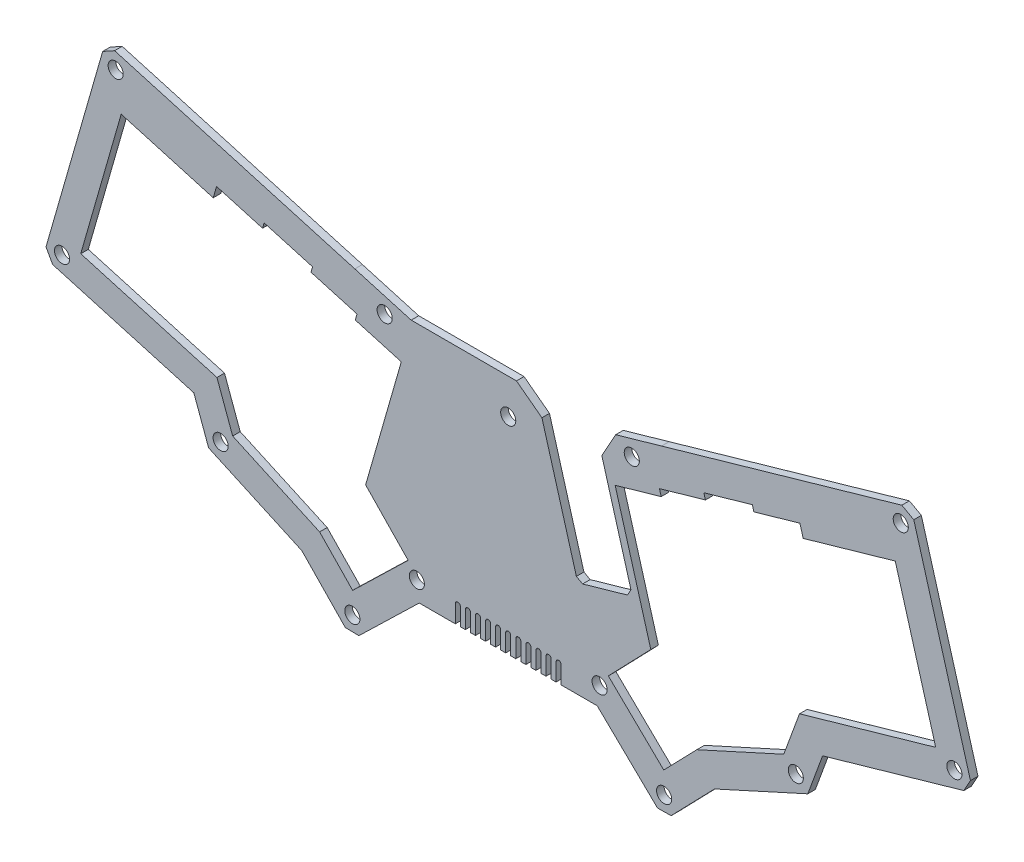
SolidWorks part; units mm, degrees
ref_plane "Plan de face" through (0, 0, 0) normal (0, 0, 1) x (1, 0, 0)
ref_plane "Plan de dessus" through (0, 0, 0) normal (0, 1, 0) x (1, 0, 0)
ref_plane "Plan de droite" through (0, 0, 0) normal (1, 0, 0) x (0, 0, -1)
sketch "Esquisse1" plane through (0, 0, 0) normal (0, 0, 1) x (1, 0, 0)
  line L0 (-121.6461, -32.0475) -> (-108.1875, -28.1884) construction
  line L1 (-108.1875, -28.1884) -> (-104.3283, -41.647) construction
  line L2 (-104.3283, -41.647) -> (-117.7869, -45.5062) construction
  line L3 (-117.7869, -45.5062) -> (-121.6461, -32.0475) construction
  line L4 (-100.1763, -37.9855) -> (-104.0355, -24.5269) construction
  line L5 (-104.0355, -24.5269) -> (-90.5769, -20.6677) construction
  line L6 (-90.5769, -20.6677) -> (-86.7177, -34.1263) construction
  line L7 (-86.7177, -34.1263) -> (-100.1763, -37.9855) construction
  line L8 (-82.5657, -30.4649) -> (-86.4249, -17.0063) construction
  line L9 (-86.4249, -17.0063) -> (-72.9663, -13.1471) construction
  line L10 (-72.9663, -13.1471) -> (-69.1071, -26.6057) construction
  line L11 (-69.1071, -26.6057) -> (-82.5657, -30.4649) construction
  line L12 (-63.6458, -27.5106) -> (-67.505, -14.0519) construction
  line L13 (-67.505, -14.0519) -> (-54.0463, -10.1927) construction
  line L14 (-54.0463, -10.1927) -> (-50.1872, -23.6514) construction
  line L15 (-50.1872, -23.6514) -> (-63.6458, -27.5106) construction
  line L16 (-44.0711, -26.8394) -> (-47.9303, -13.3808) construction
  line L17 (-47.9303, -13.3808) -> (-34.4717, -9.5216) construction
  line L18 (-34.4717, -9.5216) -> (-30.6125, -22.9802) construction
  line L19 (-30.6125, -22.9802) -> (-44.0711, -26.8394) construction
  line L20 (-25.8054, -21.6018) -> (-29.6646, -8.1432) construction
  line L21 (-29.6646, -8.1432) -> (-16.206, -4.284) construction
  line L22 (-16.206, -4.284) -> (-12.3468, -17.7426) construction
  line L23 (-12.3468, -17.7426) -> (-25.8054, -21.6018) construction
  line L24 (-116.4086, -50.3128) -> (-102.95, -46.4536) construction
  line L25 (-102.95, -46.4536) -> (-99.0908, -59.9122) construction
  line L26 (-99.0908, -59.9122) -> (-112.5494, -63.7714) construction
  line L27 (-112.5494, -63.7714) -> (-116.4086, -50.3128) construction
  line L28 (-98.798, -42.7922) -> (-85.3394, -38.933) construction
  line L29 (-85.3394, -38.933) -> (-81.4802, -52.3916) construction
  line L30 (-81.4802, -52.3916) -> (-94.9388, -56.2508) construction
  line L31 (-94.9388, -56.2508) -> (-98.798, -42.7922) construction
  line L32 (-81.1874, -35.2715) -> (-67.7288, -31.4123) construction
  line L33 (-67.7288, -31.4123) -> (-63.8696, -44.8709) construction
  line L34 (-63.8696, -44.8709) -> (-77.3282, -48.7301) construction
  line L35 (-77.3282, -48.7301) -> (-81.1874, -35.2715) construction
  line L36 (-62.2675, -32.3172) -> (-48.8089, -28.458) construction
  line L37 (-48.8089, -28.458) -> (-44.9497, -41.9166) construction
  line L38 (-44.9497, -41.9166) -> (-58.4083, -45.7758) construction
  line L39 (-58.4083, -45.7758) -> (-62.2675, -32.3172) construction
  line L40 (-42.6928, -31.646) -> (-29.2342, -27.7869) construction
  line L41 (-29.2342, -27.7869) -> (-25.375, -41.2455) construction
  line L42 (-25.375, -41.2455) -> (-38.8336, -45.1047) construction
  line L43 (-38.8336, -45.1047) -> (-42.6928, -31.646) construction
  line L44 (-24.4271, -26.4084) -> (-10.9685, -22.5492) construction
  line L45 (-10.9685, -22.5492) -> (-7.1093, -36.0078) construction
  line L46 (-7.1093, -36.0078) -> (-20.5679, -39.867) construction
  line L47 (-20.5679, -39.867) -> (-24.4271, -26.4084) construction
  line L48 (-19.1896, -44.6737) -> (-5.731, -40.8145) construction
  line L49 (-5.731, -40.8145) -> (-1.8718, -54.2731) construction
  line L50 (-1.8718, -54.2731) -> (-15.3304, -58.1323) construction
  line L51 (-15.3304, -58.1323) -> (-19.1896, -44.6737) construction
  line L52 (-37.4554, -49.9113) -> (-23.9967, -46.0521) construction
  line L53 (-23.9967, -46.0521) -> (-20.1376, -59.5107) construction
  line L54 (-20.1376, -59.5107) -> (-33.5962, -63.3699) construction
  line L55 (-33.5962, -63.3699) -> (-37.4554, -49.9113) construction
  line L56 (-57.03, -50.5825) -> (-43.5714, -46.7233) construction
  line L57 (-43.5714, -46.7233) -> (-39.7122, -60.1819) construction
  line L58 (-39.7122, -60.1819) -> (-53.1708, -64.0411) construction
  line L59 (-53.1708, -64.0411) -> (-57.03, -50.5825) construction
  line L60 (-75.9499, -53.5368) -> (-62.4913, -49.6776) construction
  line L61 (-62.4913, -49.6776) -> (-58.6321, -63.1362) construction
  line L62 (-58.6321, -63.1362) -> (-72.0908, -66.9954) construction
  line L63 (-72.0908, -66.9954) -> (-75.9499, -53.5368) construction
  line L64 (-93.5605, -61.0574) -> (-80.1019, -57.1982) construction
  line L65 (-80.1019, -57.1982) -> (-76.2427, -70.6569) construction
  line L66 (-76.2427, -70.6569) -> (-89.7013, -74.516) construction
  line L67 (-89.7013, -74.516) -> (-93.5605, -61.0574) construction
  line L68 (-111.1711, -68.5781) -> (-97.7125, -64.7189) construction
  line L69 (-97.7125, -64.7189) -> (-93.8533, -78.1775) construction
  line L70 (-93.8533, -78.1775) -> (-107.3119, -82.0367) construction
  line L71 (-107.3119, -82.0367) -> (-111.1711, -68.5781) construction
  line L72 (-79.0181, -77.3048) -> (-65.5595, -73.4456) construction
  line L73 (-65.5595, -73.4456) -> (-61.7003, -86.9042) construction
  line L74 (-61.7003, -86.9042) -> (-75.1589, -90.7634) construction
  line L75 (-75.1589, -90.7634) -> (-79.0181, -77.3048) construction
  line L76 (-99.4001, -88.1351) -> (-87.3916, -80.9362)
  line L77 (-87.3916, -80.9362) -> (-80.1927, -92.9448)
  line L78 (-80.1927, -92.9448) -> (-92.2012, -100.1436)
  line L79 (-92.2012, -100.1436) -> (-99.4001, -88.1351)
  line L80 (-120.0498, -100.4367) -> (-110.317, -90.3719)
  line L81 (-110.317, -90.3719) -> (-100.2522, -100.1047)
  line L82 (-100.2522, -100.1047) -> (-109.985, -110.1695)
  line L83 (-109.985, -110.1695) -> (-120.0498, -100.4367)
  line L86 (0.634, -55.7756) -> (-52.9527, -71.1413) construction
  line L89 (-59.2205, -88.2424) -> (-52.9527, -71.1413) construction
  line L96 (-93.4066, -103.0586) -> (-59.4637, -88.3612) construction
  line L97 (-105.418, -115.2057) -> (-93.9754, -103.3509) construction
  line L98 (-126.5332, -96.9919) -> (-107.5003, -115.385) construction
  line L99 (-167.7972, -50.1766) -> (-183.2082, -64.014) construction
  line L100 (-106.3822, -25.4572) -> (-123.6848, -30.4187) construction
  line L101 (-72.1178, -10.6906) -> (-88.4663, -15.3784) construction
  line L102 (-53.2337, -7.6163) -> (-70.5393, -12.5786) construction
  line L103 (-33.6604, -6.9452) -> (-50.9661, -11.9075) construction
  line L104 (-15.3965, -1.7081) -> (-31.745, -6.396) construction
  line L105 (0.5403, -55.2132) -> (-14.6896, -2.0999) construction
  line L106 (-16.199, -60.6113) -> (0.1495, -55.9235) construction
  line L107 (-52.7198, -71.0835) -> (-18.1144, -61.1606) construction
  line L108 (-59.1184, -88.0534) -> (-52.9674, -71.2752) construction
  line L109 (-183.2082, -64.014) -> (-173.1824, -64.9357) construction
  line L113 (-102.2678, -134.438) -> (-84.7238, -116.3191) construction
  line L114 (-84.7238, -116.3191) -> (-47.2969, -99.2981) construction
  line L115 (-47.2969, -99.2981) -> (-41.4917, -83.4594) construction
  line L116 (14.3812, -67.4381) -> (-41.4917, -83.4594) construction
  line L117 (17.8093, -61.2536) -> (-5.1371, 18.7701) construction
  line L122 (-11.3217, 22.1985) -> (-107.4545, -5.3614) construction
  line L129 (-167.7953, -27.6055) -> (-167.7953, -64.7189) construction
  line L130 (-242.0685, -103.8419) -> (-276.37, -88.2424) construction
  line L131 (-229.5108, -116.8112) -> (-242.0685, -103.8419) construction
  line L138 (-208.9328, -96.8551) -> (-229.5108, -116.8112) construction
  line L139 (-225.5107, -79.6567) -> (-208.9328, -96.8551) construction
  line L140 (-109.3352, -134.5492) -> (-102.2678, -134.438) construction
  line L142 (-5.1371, 18.7701) -> (-11.3217, 22.1985) construction
  line L143 (-211.4691, -30.6868) -> (-225.5107, -79.6567) construction
  line L147 (-114.18, -7.2899) -> (-107.4545, -5.3614) construction
  line L148 (-114.18, -7.2899) -> (-123.7936, -10.0465) construction
  line L154 (-4.3102, 15.8863) -> (-127.3606, -19.3904) construction
  line L155 (-131.531, -101.8802) -> (-105.9239, -126.7133) construction
  line L156 (-105.9239, -126.7133) -> (-89.4162, -109.6646) construction
  line L157 (-128.0696, -96.8789) -> (-106.0575, -118.2258)
  line L158 (-106.0575, -118.2258) -> (-92.9354, -104.6737)
  line L159 (-92.9354, -104.6737) -> (-58.4256, -88.9794)
  line L160 (-58.4256, -88.9794) -> (-52.1886, -71.9625)
  line L161 (1.8709, -56.4612) -> (-52.1886, -71.9625)
  line L162 (1.8709, -56.4612) -> (-14.1861, -0.4639)
  line L163 (-14.1861, -0.4639) -> (-50.7166, -10.9388)
  line L164 (-50.7166, -10.9388) -> (-52.026, -6.3725)
  line L165 (-52.026, -6.3725) -> (-70.2913, -11.61)
  line L166 (-70.2913, -11.61) -> (-70.911, -9.4488)
  line L167 (-70.911, -9.4488) -> (-90.1377, -14.9608)
  line L168 (-90.1377, -14.9608) -> (-89.5177, -17.1231)
  line L169 (-89.5177, -17.1231) -> (-107.783, -22.3606)
  line L170 (-107.783, -22.3606) -> (-107.0938, -24.7639)
  line L171 (-107.0938, -24.7639) -> (-125.3583, -30.0011)
  line L172 (-125.3583, -30.0011) -> (-111.2001, -79.378)
  line L173 (-111.2001, -79.378) -> (-127.3777, -96.1611)
  line L174 (-89.4162, -109.6646) -> (-53.6562, -93.4017) construction
  line L175 (-53.6562, -93.4017) -> (-47.6042, -76.8897) construction
  line L176 (9.2923, -60.5749) -> (-47.6042, -76.8897) construction
  line L177 (9.2923, -60.5749) -> (-12.0005, 13.6817) construction
  line L178 (-229.7336, -25.4495) -> (-211.4691, -30.6868) construction
  line L179 (-229.0444, -23.0462) -> (-229.7336, -25.4495) construction
  line L180 (-173.1824, -64.9357) -> (-167.7972, -60.1004) construction
  line L181 (-247.3097, -17.8087) -> (-229.0444, -23.0462) construction
  line L185 (17.8093, -61.2536) -> (14.3812, -67.4381) construction
  line L186 (-183.2987, -65.7677) -> (-173.2729, -66.6895) construction
  line L187 (-173.2729, -66.6895) -> (-167.8052, -74.7882) construction
  line L190 (-246.6897, -15.6465) -> (-247.3097, -17.8087) construction
  line L191 (-263.9939, -10.6857) -> (-246.6897, -15.6465) construction
  line L192 (-264.6136, -12.8469) -> (-263.9939, -10.6857) construction
  line L193 (-282.8789, -7.6094) -> (-264.6136, -12.8469) construction
  line L194 (-284.1883, -12.1757) -> (-282.8789, -7.6094) construction
  line L195 (-320.7188, -1.7008) -> (-284.1883, -12.1757) construction
  line L196 (-336.2245, -55.7756) -> (-320.7188, -1.7008) construction
  line L197 (-183.2987, -65.7677) -> (-167.8052, -88.0782) construction
  line L198 (-181.8414, -71.5322) -> (-174.8684, -81.0171) construction
  line L199 (-174.8684, -81.0171) -> (-178.3549, -83.9622) construction
  line L200 (-344.8828, -60.5749) -> (-323.5901, 13.6817) construction
  line L201 (-344.8828, -60.5749) -> (-287.9863, -76.8897) construction
  line L202 (-281.9343, -93.4017) -> (-287.9863, -76.8897) construction
  line L203 (-246.1743, -109.6646) -> (-281.9343, -93.4017) construction
  line L204 (-224.3904, -79.378) -> (-208.2128, -96.1611)
  line L205 (-210.2322, -30.0011) -> (-224.3904, -79.378)
  line L206 (-228.4967, -24.7639) -> (-210.2322, -30.0011)
  line L207 (-227.8075, -22.3606) -> (-228.4967, -24.7639)
  line L208 (-246.0728, -17.1231) -> (-227.8075, -22.3606)
  line L209 (-245.4528, -14.9608) -> (-246.0728, -17.1231)
  line L210 (-264.6796, -9.4488) -> (-245.4528, -14.9608)
  line L211 (-265.2993, -11.61) -> (-264.6796, -9.4488)
  line L212 (-283.5645, -6.3725) -> (-265.2993, -11.61)
  line L213 (-284.8739, -10.9388) -> (-283.5645, -6.3725)
  line L217 (0.634, -55.7756) -> (-14.8717, -1.7008) construction
  line L220 (-14.8717, -1.7008) -> (-51.4022, -12.1757) construction
  line L221 (-51.4022, -12.1757) -> (-52.7116, -7.6094) construction
  line L222 (-52.7116, -7.6094) -> (-70.9769, -12.8469) construction
  line L223 (-70.9769, -12.8469) -> (-71.5966, -10.6857) construction
  line L224 (-71.5966, -10.6857) -> (-88.9008, -15.6465) construction
  line L225 (-88.9008, -15.6465) -> (-88.2808, -17.8087) construction
  line L226 (-88.2808, -17.8087) -> (-106.5461, -23.0462) construction
  line L227 (-106.5461, -23.0462) -> (-105.8569, -25.4495) construction
  line L228 (-105.8569, -25.4495) -> (-124.1214, -30.6868) construction
  line L231 (-124.1214, -30.6868) -> (-110.0799, -79.6567) construction
  line L232 (-110.0799, -79.6567) -> (-126.6577, -96.8551) construction
  line L233 (-126.6577, -96.8551) -> (-106.0797, -116.8112) construction
  line L234 (-106.0797, -116.8112) -> (-93.522, -103.8419) construction
  line L235 (-93.522, -103.8419) -> (-59.2205, -88.2424) construction
  line L236 (-321.4044, -0.4639) -> (-284.8739, -10.9388)
  line L237 (-337.4614, -56.4612) -> (-321.4044, -0.4639)
  line L238 (-337.4614, -56.4612) -> (-283.4019, -71.9625)
  line L239 (-277.1649, -88.9794) -> (-283.4019, -71.9625)
  line L240 (-242.6551, -104.6737) -> (-277.1649, -88.9794)
  line L241 (-229.5331, -118.2258) -> (-242.6551, -104.6737)
  line L242 (-208.2366, -97.573) -> (-229.5331, -118.2258)
  line L243 (-229.6666, -126.7133) -> (-246.1743, -109.6646) construction
  line L244 (-204.0596, -101.8802) -> (-229.6666, -126.7133) construction
  line L245 (-331.2803, 15.8863) -> (-208.2299, -19.3904) construction
  line L246 (-178.3549, -83.9622) -> (-185.8788, -75.0552) construction
  line L247 (-185.8788, -75.0552) -> (-181.8414, -71.5322) construction
  line L248 (-176.7625, -46.6332) -> (-185.5498, -54.5291) construction
  line L249 (-185.5498, -54.5291) -> (-181.1562, -59.4188) construction
  line L250 (-181.1562, -59.4188) -> (-172.3689, -51.5229) construction
  line L251 (-276.4721, -88.0534) -> (-282.6232, -71.2752) construction
  line L252 (-282.8707, -71.0835) -> (-317.4761, -61.1606) construction
  line L253 (-319.3915, -60.6113) -> (-335.74, -55.9235) construction
  line L254 (-336.1309, -55.2132) -> (-320.9009, -2.0999) construction
  line L255 (-320.194, -1.7081) -> (-303.8455, -6.396) construction
  line L256 (-301.9301, -6.9452) -> (-284.6245, -11.9075) construction
  line L257 (-282.3568, -7.6163) -> (-265.0512, -12.5786) construction
  line L258 (-263.4727, -10.6906) -> (-247.1242, -15.3784) construction
  line L259 (-229.2083, -25.4572) -> (-211.9057, -30.4187) construction
  line L260 (-172.3689, -51.5229) -> (-176.7625, -46.6332) construction
  line L261 (-209.0573, -96.9919) -> (-228.0902, -115.385) construction
  line L262 (-230.1725, -115.2057) -> (-241.6151, -103.3509) construction
  line L263 (-242.1839, -103.0586) -> (-276.1268, -88.3612) construction
  line L264 (-276.37, -88.2424) -> (-282.6379, -71.1413) construction
  line L265 (-336.2245, -55.7756) -> (-282.6379, -71.1413) construction
  line L268 (-353.3998, -61.2536) -> (-349.9717, -67.4381) construction
  line L274 (-221.4105, -7.2899) -> (-206.0252, -11.7015) construction
  line L275 (-221.4105, -7.2899) -> (-228.136, -5.3614) construction
  line L276 (-330.4534, 18.7701) -> (-324.2688, 22.1985) construction
  line L277 (-226.2553, -134.5492) -> (-233.3227, -134.438) construction
  line L281 (-324.2688, 22.1985) -> (-228.136, -5.3614) construction
  line L282 (-353.3998, -61.2536) -> (-330.4534, 18.7701) construction
  line L283 (-349.9717, -67.4381) -> (-294.0988, -83.4594) construction
  line L284 (-288.2936, -99.2981) -> (-294.0988, -83.4594) construction
  line L285 (-250.8667, -116.3191) -> (-288.2936, -99.2981) construction
  line L286 (-233.3227, -134.438) -> (-250.8667, -116.3191) construction
  line L288 (-225.6055, -110.1695) -> (-215.5407, -100.4367) construction
  line L289 (-235.3383, -100.1047) -> (-225.6055, -110.1695) construction
  line L290 (-225.2735, -90.3719) -> (-235.3383, -100.1047) construction
  line L291 (-215.5407, -100.4367) -> (-225.2735, -90.3719) construction
  line L292 (-243.3893, -100.1436) -> (-236.1904, -88.1351) construction
  line L293 (-255.3978, -92.9448) -> (-243.3893, -100.1436) construction
  line L294 (-248.1989, -80.9362) -> (-255.3978, -92.9448) construction
  line L295 (-236.1904, -88.1351) -> (-248.1989, -80.9362) construction
  line L296 (-260.4316, -90.7634) -> (-256.5724, -77.3048) construction
  line L297 (-273.8902, -86.9042) -> (-260.4316, -90.7634) construction
  line L298 (-270.031, -73.4456) -> (-273.8902, -86.9042) construction
  line L299 (-256.5724, -77.3048) -> (-270.031, -73.4456) construction
  line L300 (-228.2786, -82.0367) -> (-224.4194, -68.5781) construction
  line L301 (-241.7372, -78.1775) -> (-228.2786, -82.0367) construction
  line L302 (-237.878, -64.7189) -> (-241.7372, -78.1775) construction
  line L303 (-224.4194, -68.5781) -> (-237.878, -64.7189) construction
  line L304 (-245.8892, -74.516) -> (-242.03, -61.0574) construction
  line L305 (-259.3478, -70.6569) -> (-245.8892, -74.516) construction
  line L306 (-255.4886, -57.1982) -> (-259.3478, -70.6569) construction
  line L307 (-242.03, -61.0574) -> (-255.4886, -57.1982) construction
  line L308 (-263.4998, -66.9954) -> (-259.6406, -53.5368) construction
  line L309 (-276.9584, -63.1362) -> (-263.4998, -66.9954) construction
  line L310 (-273.0992, -49.6776) -> (-276.9584, -63.1362) construction
  line L311 (-259.6406, -53.5368) -> (-273.0992, -49.6776) construction
  line L312 (-282.4197, -64.0411) -> (-278.5605, -50.5825) construction
  line L313 (-295.8783, -60.1819) -> (-282.4197, -64.0411) construction
  line L314 (-292.0191, -46.7233) -> (-295.8783, -60.1819) construction
  line L315 (-278.5605, -50.5825) -> (-292.0191, -46.7233) construction
  line L316 (-301.9944, -63.3699) -> (-298.1352, -49.9113) construction
  line L317 (-315.453, -59.5107) -> (-301.9944, -63.3699) construction
  line L318 (-311.5938, -46.0521) -> (-315.453, -59.5107) construction
  line L319 (-298.1352, -49.9113) -> (-311.5938, -46.0521) construction
  line L320 (-320.2601, -58.1323) -> (-316.4009, -44.6737) construction
  line L321 (-333.7187, -54.2731) -> (-320.2601, -58.1323) construction
  line L322 (-329.8595, -40.8145) -> (-333.7187, -54.2731) construction
  line L323 (-316.4009, -44.6737) -> (-329.8595, -40.8145) construction
  line L324 (-315.0226, -39.867) -> (-311.1634, -26.4084) construction
  line L325 (-328.4812, -36.0078) -> (-315.0226, -39.867) construction
  line L326 (-324.622, -22.5492) -> (-328.4812, -36.0078) construction
  line L327 (-311.1634, -26.4084) -> (-324.622, -22.5492) construction
  line L328 (-296.7569, -45.1047) -> (-292.8977, -31.646) construction
  line L329 (-310.2155, -41.2455) -> (-296.7569, -45.1047) construction
  line L330 (-306.3563, -27.7869) -> (-310.2155, -41.2455) construction
  line L331 (-292.8977, -31.646) -> (-306.3563, -27.7869) construction
  line L332 (-277.1822, -45.7758) -> (-273.323, -32.3172) construction
  line L333 (-290.6408, -41.9166) -> (-277.1822, -45.7758) construction
  line L334 (-286.7817, -28.458) -> (-290.6408, -41.9166) construction
  line L335 (-273.323, -32.3172) -> (-286.7817, -28.458) construction
  line L336 (-258.2623, -48.7301) -> (-254.4031, -35.2715) construction
  line L337 (-271.7209, -44.8709) -> (-258.2623, -48.7301) construction
  line L338 (-267.8617, -31.4123) -> (-271.7209, -44.8709) construction
  line L339 (-254.4031, -35.2715) -> (-267.8617, -31.4123) construction
  line L340 (-240.6517, -56.2508) -> (-236.7925, -42.7922) construction
  line L341 (-254.1103, -52.3916) -> (-240.6517, -56.2508) construction
  line L342 (-250.2511, -38.933) -> (-254.1103, -52.3916) construction
  line L343 (-236.7925, -42.7922) -> (-250.2511, -38.933) construction
  line L344 (-223.0411, -63.7714) -> (-219.1819, -50.3128) construction
  line L345 (-236.4997, -59.9122) -> (-223.0411, -63.7714) construction
  line L346 (-232.6405, -46.4536) -> (-236.4997, -59.9122) construction
  line L347 (-219.1819, -50.3128) -> (-232.6405, -46.4536) construction
  line L348 (-323.2438, -17.7426) -> (-309.7851, -21.6018) construction
  line L349 (-319.3846, -4.284) -> (-323.2438, -17.7426) construction
  line L350 (-305.926, -8.1432) -> (-319.3846, -4.284) construction
  line L351 (-309.7851, -21.6018) -> (-305.926, -8.1432) construction
  line L352 (-304.978, -22.9802) -> (-291.5194, -26.8394) construction
  line L353 (-301.1188, -9.5216) -> (-304.978, -22.9802) construction
  line L354 (-287.6602, -13.3808) -> (-301.1188, -9.5216) construction
  line L355 (-291.5194, -26.8394) -> (-287.6602, -13.3808) construction
  line L356 (-285.4034, -23.6514) -> (-271.9448, -27.5106) construction
  line L357 (-281.5442, -10.1927) -> (-285.4034, -23.6514) construction
  line L358 (-268.0856, -14.0519) -> (-281.5442, -10.1927) construction
  line L359 (-271.9448, -27.5106) -> (-268.0856, -14.0519) construction
  line L360 (-266.4834, -26.6057) -> (-253.0248, -30.4649) construction
  line L361 (-262.6242, -13.1471) -> (-266.4834, -26.6057) construction
  line L362 (-249.1656, -17.0063) -> (-262.6242, -13.1471) construction
  line L363 (-253.0248, -30.4649) -> (-249.1656, -17.0063) construction
  line L364 (-248.8728, -34.1263) -> (-235.4142, -37.9855) construction
  line L365 (-245.0136, -20.6677) -> (-248.8728, -34.1263) construction
  line L366 (-231.555, -24.5269) -> (-245.0136, -20.6677) construction
  line L367 (-235.4142, -37.9855) -> (-231.555, -24.5269) construction
  line L368 (-217.8036, -45.5062) -> (-213.9444, -32.0475) construction
  line L369 (-231.2622, -41.647) -> (-217.8036, -45.5062) construction
  line L370 (-227.4031, -28.1884) -> (-231.2622, -41.647) construction
  line L371 (-213.9444, -32.0475) -> (-227.4031, -28.1884) construction
  line L372 (-226.2553, -134.5492) -> (-194.0347, -103.3509) construction
  line L373 (-109.3352, -134.5492) -> (-141.5559, -103.3509) construction
  line L374 (-141.5559, -103.3509) -> (-194.0347, -103.3509) construction
  line L375 (-167.7972, -50.1766) -> (-152.3861, -64.014) construction
  line L376 (-162.4119, -64.9357) -> (-167.7972, -60.1004) construction
  line L377 (-162.3376, -66.6895) -> (-167.8052, -74.7882) construction
  line L378 (-152.3118, -65.7677) -> (-167.8052, -88.0782) construction
  line L379 (-163.2254, -51.5229) -> (-158.8318, -46.6332) construction
  line L380 (-154.4381, -59.4188) -> (-163.2254, -51.5229) construction
  line L381 (-150.0445, -54.5291) -> (-154.4381, -59.4188) construction
  line L382 (-158.8318, -46.6332) -> (-150.0445, -54.5291) construction
  line L383 (-149.7316, -75.0552) -> (-153.7691, -71.5322) construction
  line L384 (-157.2555, -83.9622) -> (-149.7316, -75.0552) construction
  line L385 (-160.742, -81.0171) -> (-157.2555, -83.9622) construction
  line L386 (-153.7691, -71.5322) -> (-160.742, -81.0171) construction
  line L387 (-152.3118, -65.7677) -> (-162.3376, -66.6895) construction
  line L388 (-152.3861, -64.014) -> (-162.4119, -64.9357) construction
  line L389 (-206.0252, -11.7015) -> (-129.5654, -11.7015) construction
  line L390 (-119.0708, -62.7964) -> (-130.6498, -22.4155)
  line L391 (-123.5545, -47.16) -> (-127.4136, -33.7014) construction
  line L392 (-120.442, -65.2702) -> (-138.2688, -70.3819)
  line L393 (-140.7426, -69.0107) -> (-154.4194, -21.3141)
  line L394 (-167.1758, -11.7015) -> (-206.0252, -11.7015) construction
  line L395 (-154.4194, -21.3141) -> (-167.1758, -11.7015) construction
  line L396 (-123.7936, -10.0465) -> (-130.6498, -22.4155) construction
  line L397 (-138.2688, -70.3819) -> (-140.7426, -69.0107)
  line L398 (-119.0708, -62.7964) -> (-120.442, -65.2702)
  line L399 (-129.5654, -11.7015) -> (-123.7936, -10.0465) construction
  line L400 (-165.8487, -12.7015) -> (-206.1657, -12.7015) construction
  line L401 (-221.6861, -8.2511) -> (-206.1657, -12.7015) construction
  line L402 (-221.6861, -8.2511) -> (-228.4116, -6.3226) construction
  line L403 (-324.1462, 21.1231) -> (-228.4116, -6.3226) construction
  line L404 (-329.6063, 18.0963) -> (-324.1462, 21.1231) construction
  line L405 (-352.3244, -61.1311) -> (-329.6063, 18.0963) construction
  line L406 (-352.3244, -61.1311) -> (-349.2979, -66.591) construction
  line L407 (-349.2979, -66.591) -> (-293.3347, -82.6382) construction
  line L408 (-287.4987, -98.561) -> (-293.3347, -82.6382) construction
  line L409 (-250.2802, -115.4872) -> (-287.4987, -98.561) construction
  line L410 (-232.8926, -133.4446) -> (-250.2802, -115.4872) construction
  line L411 (-226.6535, -133.5428) -> (-232.8926, -133.4446) construction
  line L412 (-226.6535, -133.5428) -> (-194.4395, -102.3509) construction
  line L413 (-141.1511, -102.3509) -> (-194.4395, -102.3509) construction
  line L414 (-108.937, -133.5428) -> (-141.1511, -102.3509) construction
  line L415 (-108.937, -133.5428) -> (-102.6979, -133.4446) construction
  line L416 (-102.6979, -133.4446) -> (-85.3104, -115.4872) construction
  line L417 (-85.3104, -115.4872) -> (-48.0918, -98.561) construction
  line L418 (-48.0918, -98.561) -> (-42.2558, -82.6382) construction
  line L419 (13.7074, -66.591) -> (-42.2558, -82.6382) construction
  line L420 (16.7339, -61.1311) -> (13.7074, -66.591) construction
  line L421 (16.7339, -61.1311) -> (-5.9842, 18.0963) construction
  line L422 (-5.9842, 18.0963) -> (-11.4443, 21.1231) construction
  line L423 (-11.4443, 21.1231) -> (-107.1789, -6.3226) construction
  line L424 (-113.9044, -8.2511) -> (-107.1789, -6.3226) construction
  line L425 (-113.9044, -8.2511) -> (-124.4792, -11.2834) construction
  line L426 (-167.1758, -12.7015) -> (-206.1657, -12.7015) construction
  line L427 (-113.9044, -8.2511) -> (-123.5179, -11.0078) construction
  line L428 (-165.8487, -12.7015) -> (-154.4194, -21.3141) construction
  line L429 (-130.6498, -22.4155) -> (-124.4792, -11.2834) construction
  line L430 (-208.2366, -97.573) -> (-207.4919, -96.8551)
  line L431 (-207.4919, -96.8551) -> (-208.2128, -96.1611)
  line L432 (-127.3777, -96.1611) -> (-128.0696, -96.8789)
  line L433 (-221.9618, -9.2124) -> (-206.3062, -13.7015)
  line L434 (-164.5217, -13.7015) -> (-206.3062, -13.7015)
  line L435 (-166.1833, -13.7015) -> (-155.2884, -21.9114) construction
  line L436 (-141.5897, -69.6845) -> (-155.2884, -21.9114) construction
  line L437 (-138.3914, -71.4574) -> (-141.5897, -69.6845) construction
  line L438 (-119.7682, -66.1172) -> (-138.3914, -71.4574) construction
  line L439 (-117.9954, -62.9189) -> (-119.7682, -66.1172) construction
  line L440 (-117.9954, -62.9189) -> (-129.5744, -22.538) construction
  line L441 (-129.5744, -22.538) -> (-123.8054, -12.1305) construction
  line L442 (-113.6287, -9.2124) -> (-125.1648, -12.5203)
  line L443 (-113.6287, -9.2124) -> (-106.9033, -7.2839)
  line L444 (-11.5669, 20.0477) -> (-106.9033, -7.2839)
  line L445 (-6.8313, 17.4225) -> (-11.5669, 20.0477)
  line L446 (15.6584, -61.0086) -> (-6.8313, 17.4225)
  line L447 (15.6584, -61.0086) -> (13.0336, -65.7439)
  line L448 (13.0336, -65.7439) -> (-43.0198, -81.817)
  line L449 (-48.8867, -97.824) -> (-43.0198, -81.817)
  line L450 (-85.8969, -114.6554) -> (-48.8867, -97.824)
  line L451 (-103.128, -132.4513) -> (-85.8969, -114.6554)
  line L452 (-108.5388, -132.5364) -> (-103.128, -132.4513)
  line L453 (-108.5388, -132.5364) -> (-132.4841, -109.3509)
  line L454 (-140.7463, -101.3509) -> (-194.8443, -101.3509) construction
  line L455 (-227.0517, -132.5364) -> (-203.1064, -109.3509)
  line L456 (-227.0517, -132.5364) -> (-232.4625, -132.4513)
  line L457 (-232.4625, -132.4513) -> (-249.6936, -114.6554)
  line L458 (-249.6936, -114.6554) -> (-286.7038, -97.824)
  line L459 (-286.7038, -97.824) -> (-292.5707, -81.817)
  line L460 (-348.6241, -65.7439) -> (-292.5707, -81.817)
  line L461 (-351.2489, -61.0086) -> (-348.6241, -65.7439)
  line L462 (-351.2489, -61.0086) -> (-328.7592, 17.4225)
  line L463 (-328.7592, 17.4225) -> (-324.0237, 20.0477)
  line L464 (-324.0237, 20.0477) -> (-228.6872, -7.2839)
  line L465 (-221.9618, -9.2124) -> (-228.6872, -7.2839)
  line L466 (-166.1833, -13.7015) -> (-206.3062, -13.7015) construction
  line L467 (-113.6287, -9.2124) -> (-123.8054, -12.1305) construction
  line L468 (-130.6498, -22.4155) -> (-125.1648, -12.5203)
  line L469 (-154.4194, -21.3141) -> (-164.5217, -13.7015)
  line L470 (-132.4841, -109.3509) -> (-203.1064, -109.3509)
  line L471 (-140.7463, -109.3509) -> (-194.8443, -109.3509) construction
  line L473 (-227.0517, -132.5364) -> (-194.8443, -101.3509) construction
  line L474 (-108.5388, -132.5364) -> (-140.7463, -101.3509) construction
  circle A2 centre (-12.0005, 13.6817) radius 1.6 construction
  circle A3 centre (-12.0005, 13.6817) radius 3
  circle A4 centre (-118.7579, -16.9241) radius 3
  circle A5 centre (9.2923, -60.5749) radius 3
  circle A6 centre (-53.6562, -93.4017) radius 3
  circle A7 centre (-105.9239, -126.7133) radius 3
  circle A8 centre (-131.531, -101.8802) radius 3
  circle A10 centre (-147.4897, -45.973) radius 1.6 construction
  circle A11 centre (-323.5901, 13.6817) radius 3
  circle A12 centre (-188.1008, -45.973) radius 1.6 construction
  circle A14 centre (-204.0596, -101.8802) radius 3
  circle A15 centre (-229.6666, -126.7133) radius 3
  circle A16 centre (-281.9343, -93.4017) radius 3
  circle A17 centre (-344.8828, -60.5749) radius 3
  circle A18 centre (-216.8326, -16.9241) radius 3
  circle A19 centre (-323.5901, 13.6817) radius 1.6 construction
  circle A20 centre (-167.7953, -27.6055) radius 3
  point P138 (-167.7953, -27.6055)
  point P139 (-6.5153, 23.5764)
  point P150 (-169.1046, -23.0392)
  point P200 (19.1875, -66.0599)
  point P203 (-141.5228, -71.3355)
  point P204 (-141.5228, 1.5705)
  point P263 (-133.4062, -12.8029)
  point P264 (-118.5195, -64.7189)
  point P283 (-140.1914, -70.9332)
  point P284 (-157.1758, -11.7015)
  point P405 (-354.778, -66.0599)
  point P406 (-329.0752, 23.5764)
  dimension "D3" = 3.2
  dimension "D4" = 6
  dimension "D6" = 6
  dimension "D7" = 6
  dimension "D8" = 6
  dimension "D9" = 6
  dimension "D10" = 6
  dimension "D16" = 3.2
  dimension "D14" = 6
  dimension "D2" = 6
  dimension "D5" = 1
  dimension "D11" = 1
  dimension "D18" = 8
extrude "Boss.-Extru.1" add sketch "Esquisse1" along normal blind 3 contours L433 L465 L464 L463 L462 L461 L460 L459 L458 L457 L456 L455 L454 L453 L452 L451 L450 L449 L448 L447 L446 L445 L444 L443 L442 L441 L440 L439 L438 L437 L436 L435 L434 A18 A16 A14 L432 L173 L172 L171 L170 L169 L168 L167 L166 L165 L164
sketch "Esquisse2" plane through (0, 0, 3) normal (0, 0, 1) x (1, 0, 0)
  line L0 (-167.7953, -109.3509) -> (-167.7953, -102.3509) construction
  line L1 (-132.4841, -109.3509) -> (-203.1064, -109.3509) construction
  line L2 (-168.7953, -109.3509) -> (-168.7953, -102.3509)
  line L3 (-166.7953, -109.3509) -> (-166.7953, -102.3509)
  line L4 (-163.7953, -109.3509) -> (-163.7953, -102.3509) construction
  line L5 (-164.7953, -109.3509) -> (-164.7953, -102.3509)
  line L6 (-162.7953, -109.3509) -> (-162.7953, -102.3509)
  line L7 (-159.7953, -109.3509) -> (-159.7953, -102.3509) construction
  line L8 (-160.7953, -109.3509) -> (-160.7953, -102.3509)
  line L9 (-158.7953, -109.3509) -> (-158.7953, -102.3509)
  line L10 (-155.7953, -109.3509) -> (-155.7953, -102.3509) construction
  line L11 (-156.7953, -109.3509) -> (-156.7953, -102.3509)
  line L12 (-154.7953, -109.3509) -> (-154.7953, -102.3509)
  line L13 (-151.7953, -109.3509) -> (-151.7953, -102.3509) construction
  line L14 (-152.7953, -109.3509) -> (-152.7953, -102.3509)
  line L15 (-150.7953, -109.3509) -> (-150.7953, -102.3509)
  line L16 (-147.7953, -109.3509) -> (-147.7953, -102.3509) construction
  line L17 (-148.7953, -109.3509) -> (-148.7953, -102.3509)
  line L18 (-146.7953, -109.3509) -> (-146.7953, -102.3509)
  line L19 (-171.7953, -109.3509) -> (-171.7953, -102.3509) construction
  line L20 (-172.7953, -109.3509) -> (-172.7953, -102.3509)
  line L21 (-170.7953, -109.3509) -> (-170.7953, -102.3509)
  line L22 (-175.7953, -109.3509) -> (-175.7953, -102.3509) construction
  line L23 (-176.7953, -109.3509) -> (-176.7953, -102.3509)
  line L24 (-174.7953, -109.3509) -> (-174.7953, -102.3509)
  line L25 (-179.7953, -109.3509) -> (-179.7953, -102.3509) construction
  line L26 (-180.7953, -109.3509) -> (-180.7953, -102.3509)
  line L27 (-178.7953, -109.3509) -> (-178.7953, -102.3509)
  line L28 (-183.7953, -109.3509) -> (-183.7953, -102.3509) construction
  line L29 (-184.7953, -109.3509) -> (-184.7953, -102.3509)
  line L30 (-182.7953, -109.3509) -> (-182.7953, -102.3509)
  line L31 (-187.7953, -109.3509) -> (-187.7953, -102.3509) construction
  line L32 (-188.7953, -109.3509) -> (-188.7953, -102.3509)
  line L33 (-186.7953, -109.3509) -> (-186.7953, -102.3509)
  arc A0 (-168.7953, -109.3509) -> (-166.7953, -109.3509) centre (-167.7953, -109.3509) ccw
  arc A1 (-166.7953, -102.3509) -> (-168.7953, -102.3509) centre (-167.7953, -102.3509) ccw
  arc A2 (-164.7953, -109.3509) -> (-162.7953, -109.3509) centre (-163.7953, -109.3509) ccw
  arc A3 (-162.7953, -102.3509) -> (-164.7953, -102.3509) centre (-163.7953, -102.3509) ccw
  arc A4 (-160.7953, -109.3509) -> (-158.7953, -109.3509) centre (-159.7953, -109.3509) ccw
  arc A5 (-158.7953, -102.3509) -> (-160.7953, -102.3509) centre (-159.7953, -102.3509) ccw
  arc A6 (-156.7953, -109.3509) -> (-154.7953, -109.3509) centre (-155.7953, -109.3509) ccw
  arc A7 (-154.7953, -102.3509) -> (-156.7953, -102.3509) centre (-155.7953, -102.3509) ccw
  arc A8 (-152.7953, -109.3509) -> (-150.7953, -109.3509) centre (-151.7953, -109.3509) ccw
  arc A9 (-150.7953, -102.3509) -> (-152.7953, -102.3509) centre (-151.7953, -102.3509) ccw
  arc A10 (-148.7953, -109.3509) -> (-146.7953, -109.3509) centre (-147.7953, -109.3509) ccw
  arc A11 (-146.7953, -102.3509) -> (-148.7953, -102.3509) centre (-147.7953, -102.3509) ccw
  arc A12 (-172.7953, -109.3509) -> (-170.7953, -109.3509) centre (-171.7953, -109.3509) ccw
  arc A13 (-170.7953, -102.3509) -> (-172.7953, -102.3509) centre (-171.7953, -102.3509) ccw
  arc A14 (-176.7953, -109.3509) -> (-174.7953, -109.3509) centre (-175.7953, -109.3509) ccw
  arc A15 (-174.7953, -102.3509) -> (-176.7953, -102.3509) centre (-175.7953, -102.3509) ccw
  arc A16 (-180.7953, -109.3509) -> (-178.7953, -109.3509) centre (-179.7953, -109.3509) ccw
  arc A17 (-178.7953, -102.3509) -> (-180.7953, -102.3509) centre (-179.7953, -102.3509) ccw
  arc A18 (-184.7953, -109.3509) -> (-182.7953, -109.3509) centre (-183.7953, -109.3509) ccw
  arc A19 (-182.7953, -102.3509) -> (-184.7953, -102.3509) centre (-183.7953, -102.3509) ccw
  arc A20 (-188.7953, -109.3509) -> (-186.7953, -109.3509) centre (-187.7953, -109.3509) ccw
  arc A21 (-186.7953, -102.3509) -> (-188.7953, -102.3509) centre (-187.7953, -102.3509) ccw
  point P4 (-167.7953, -105.8509)
  point P12 (-163.7953, -105.8509)
  point P19 (-159.7953, -105.8509)
  point P26 (-155.7953, -105.8509)
  point P33 (-151.7953, -105.8509)
  point P40 (-147.7953, -105.8509)
  point P47 (-171.7953, -105.8509)
  point P54 (-175.7953, -105.8509)
  point P61 (-179.7953, -105.8509)
  point P68 (-183.7953, -105.8509)
  point P75 (-187.7953, -105.8509)
  dimension "D1" = 6
  dimension "D2" = 6
extrude "Enlèv. mat.-Extru.1" cut sketch "Esquisse2" against normal blind 10
